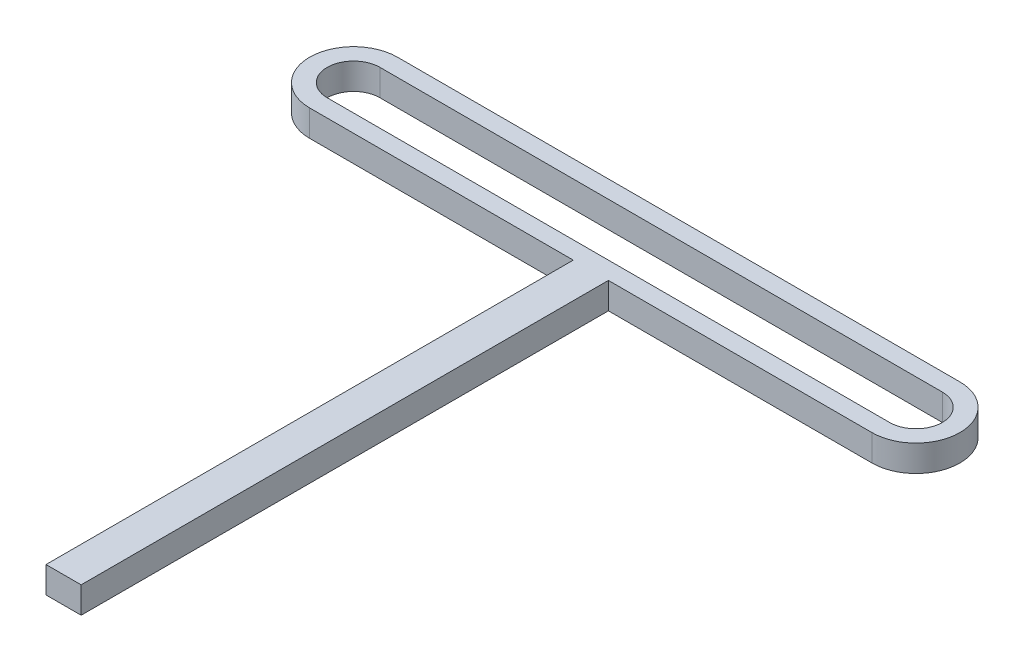
SolidWorks part; units mm, degrees
ref_plane "Front Plane" through (0, 0, 0) normal (0, 0, 1) x (1, 0, 0)
ref_plane "Top Plane" through (0, 0, 0) normal (0, 1, 0) x (1, 0, 0)
ref_plane "Right Plane" through (0, 0, 0) normal (1, 0, 0) x (0, 0, -1)
sketch "Sketch2" plane through (0, 0, 0) normal (0, 1, 0) x (1, 0, 0)
  line L0 (-32, 0) -> (32, 0) construction
  line L1 (-32, 3) -> (32, 3)
  line L2 (-32, -3) -> (32, -3)
  line L3 (-32, 5) -> (32, 5)
  line L4 (-32, -5) -> (32, -5)
  line L6 (-2, -65) -> (2, -65)
  line L7 (-2, -65) -> (-2, -5)
  line L8 (-2, -5) -> (2, -5)
  line L9 (2, -65) -> (2, -5)
  line L10 (-2, -65) -> (2, -5) construction
  line L11 (-2, -5) -> (2, -65) construction
  arc A0 (-32, 3) -> (-32, -3) centre (-32, 0) ccw
  arc A1 (32, -3) -> (32, 3) centre (32, 0) ccw
  arc A2 (32, -5) -> (32, 5) centre (32, 0) ccw
  arc A3 (-32, 5) -> (-32, -5) centre (-32, 0) ccw
  point P2 (0, 0)
  point P8 (-35, 0)
  point P9 (35, 0)
  point P16 (0, -35)
  point P21 (0, 0)
  point P22 (2, -65.1487)
  dimension "D1" = 3
  dimension "D2" = 70
  dimension "D4" = 4
  dimension "D5" = 60
  dimension "D3" = 2
extrude "Boss-Extrude1" add sketch "Sketch2" along normal blind 3 contours L3 A3 L4 A2 A1 L2 A0 L1 | L7 L8 L9 L6
